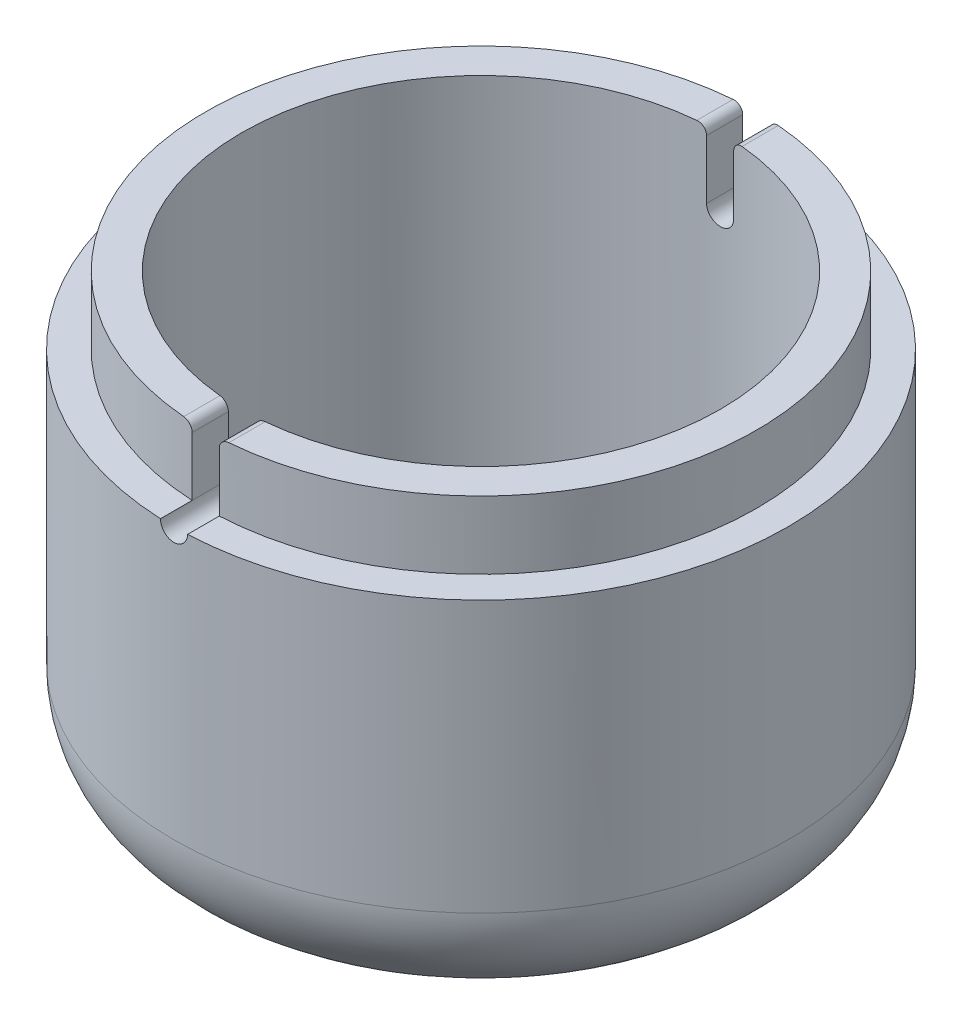
SolidWorks part; units mm, degrees
ref_plane "Plan de face" through (0, 0, 0) normal (0, 0, 1) x (1, 0, 0)
ref_plane "Plan de dessus" through (0, 0, 0) normal (0, 1, 0) x (1, 0, 0)
ref_plane "Plan de droite" through (0, 0, 0) normal (1, 0, 0) x (0, 0, -1)
sketch "Esquisse1" plane through (0, 0, 0) normal (1, 0, 0) x (0, 0, -1)
  line L0 (26.5, 49.5) -> (26.5, 7)
  line L1 (26.5, 7) -> (0, 7)
  line L2 (0, 7) -> (0, 0)
  line L3 (0, 0) -> (34, 0)
  line L4 (34, 0) -> (34, 42)
  line L5 (34, 42) -> (30.5, 42)
  line L6 (30.5, 42) -> (30.5, 49.5)
  line L7 (30.5, 49.5) -> (26.5, 49.5)
  point P2 (30.5, 42.7119)
  point P10 (16.2712, 10)
  dimension "D1" = 42.5
  dimension "D2" = 7
  dimension "D3" = 30.5
  dimension "D4" = 34
  dimension "D5" = 4
  dimension "D6" = 7.5
revolve "Révolution1" add sketch "Esquisse1" angle 360 about L2
ref_plane "Plan1" through (0, 0, 34) normal (0, 0, 1) x (1, 0, 0)
sketch "Esquisse2" plane through (0, 7, 0) normal (0, 1, 0) x (1, 0, 0)
  circle A0 centre (0, 0) radius 1.5
  circle A1 centre (15, 0) radius 1.5
  circle A2 centre (7.5, -12.9904) radius 1.5
  circle A3 centre (-7.5, -12.9904) radius 1.5
  circle A4 centre (-15, 0) radius 1.5
  circle A5 centre (-7.5, 12.9904) radius 1.5
  circle A6 centre (7.5, 12.9904) radius 1.5
  point P6 (0, 0)
  point P7 (-15.2953, -5.9269)
  point P17 (0, 0)
  point P18 (0, 0)
  dimension "D1" = 3
  dimension "D2" = 15
extrude "Enlèv. mat.-Extru.1" cut sketch "Esquisse2" against normal up to next
sketch "Esquisse3" plane through (0, 0, 34) normal (0, 0, 1) x (1, 0, 0)
  line L0 (34, 42) -> (-34, 42) construction
  line L1 (26.5, 49.5) -> (-26.5, 49.5) construction
  line L3 (-1.5, 42) -> (-1.5, 49.5)
  line L4 (-1.5, 49.5) -> (1.5, 49.5)
  line L5 (1.5, 42) -> (1.5, 49.5)
  arc A0 (-1.5, 42) -> (1.5, 42) centre (0, 42) ccw
  dimension "D1" = 3
extrude "Enlèv. mat.-Extru.2" cut sketch "Esquisse3" against normal through all
fillet "Congé1" radius 12 1 edges at (0, 0, 34)
fillet "Congé2" radius 5 1 edges at (0, 7, 26.5)
fillet "Congé3" radius 1 4 edges at (1.5, 49.5, -28.4603) (1.5, 49.5, 28.4603) (-1.5, 49.5, 28.4603) (-1.5, 49.5, -28.4603)
